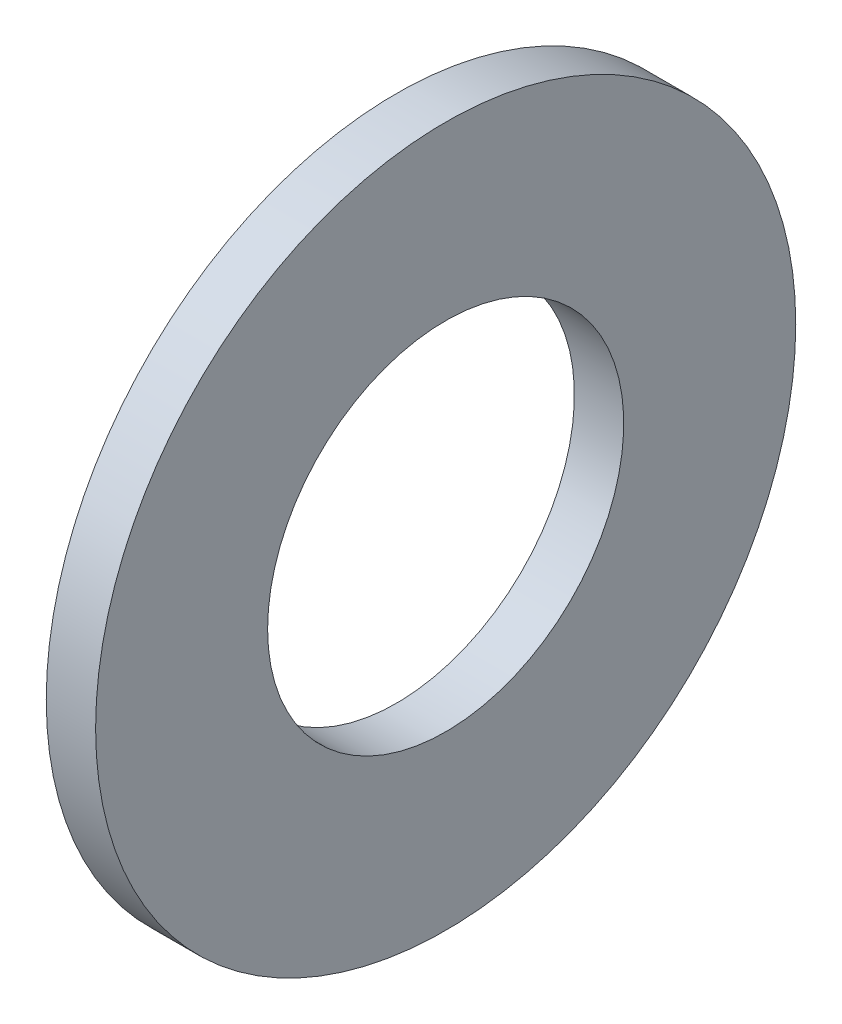
SolidWorks part; units mm, degrees
ref_plane "Plane1" through (0, 0, 0) normal (0, 0, 1) x (1, 0, 0)
ref_plane "Plane2" through (0, 0, 0) normal (0, 1, 0) x (1, 0, 0)
ref_plane "Plane3" through (0, 0, 0) normal (1, 0, 0) x (0, 0, -1)
sketch "Sketch1" plane through (0, 0, 0) normal (0, 0, 1) x (1, 0, 0)
  line L0 (-34.925, 0) -> (9.525, 0) construction
  line L1 (0, 5.9563) -> (0, 11.7094)
  line L2 (0, 11.7094) -> (-1.651, 11.7094)
  line L3 (-1.651, 11.7094) -> (-1.651, 5.9563)
  line L4 (-1.651, 5.9563) -> (0, 5.9563)
  dimension "Thickness" = 1.651
  dimension "Inside_dia" = 11.9126
  dimension "Outside_dia" = 23.4188
revolve "Base-Revolve" add sketch "Sketch1" angle 360 about L0
